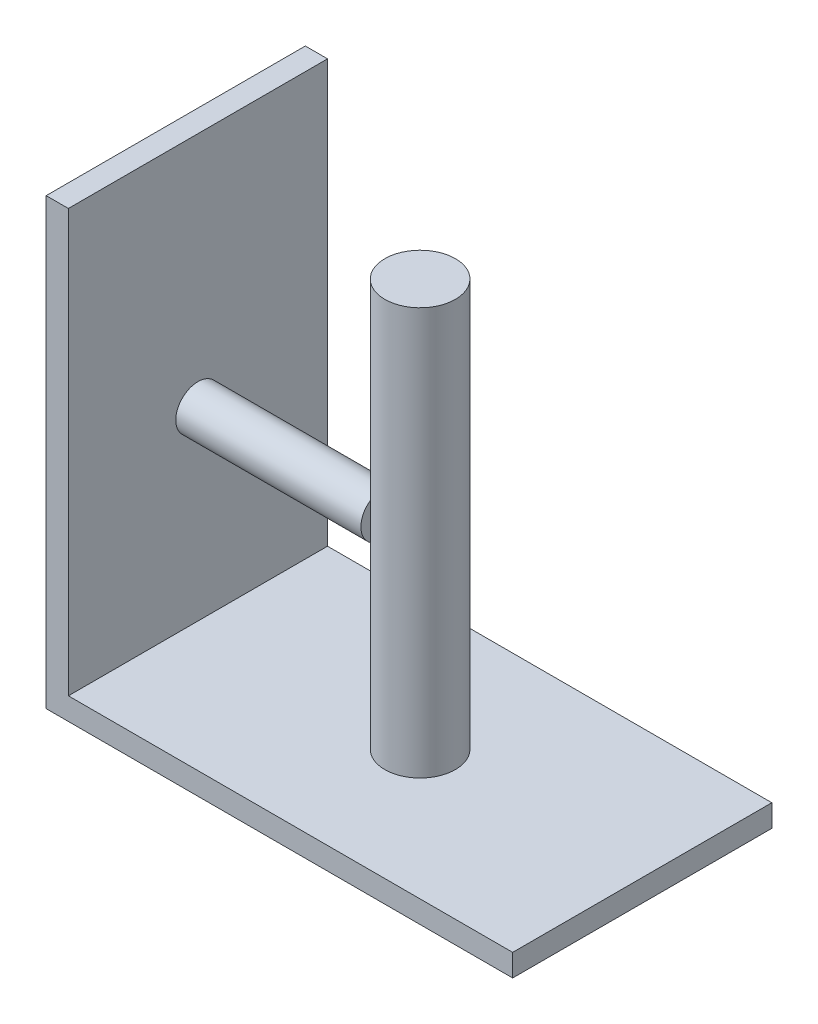
SolidWorks part; units mm, degrees
ref_plane "Alzado" through (0, 0, 0) normal (0, 0, 1) x (1, 0, 0)
ref_plane "Planta" through (0, 0, 0) normal (0, 1, 0) x (1, 0, 0)
ref_plane "Vista lateral" through (0, 0, 0) normal (1, 0, 0) x (0, 0, -1)
sketch "Croquis1" plane through (0, 0, 0) normal (0, 0, 1) x (1, 0, 0)
  line L1 (0, 0) -> (63, 0)
  line L2 (0, 0) -> (0, -3)
  line L3 (0, -3) -> (63, -3)
  line L4 (63, 0) -> (63, -3)
  line L5 (0, 0) -> (3, 0)
  line L6 (0, 0) -> (0, 57)
  line L7 (0, 57) -> (3, 57)
  line L8 (3, 0) -> (3, 57)
  dimension "D1" = 3
  dimension "D2" = 3
  dimension "D3" = 60
  dimension "D4" = 63
extrude "Saliente-Extruir1" add sketch "Croquis1" along normal mid plane 35 contours L5 L8 L7 L6 | L1 L4 L3 L2
sketch "Croquis2" plane through (3, 0, 0) normal (1, 0, 0) x (0, 0, -1)
  line L0 (-17.5, 0) -> (-17.5, 57) construction
  circle A0 centre (0, 25) radius 3
  dimension "D1" = 6
  dimension "D2" = 25
  dimension "D3" = 17.5
extrude "Saliente-Extruir2" add sketch "Croquis2" along normal blind 25
sketch "Croquis3" plane through (0, 0, 0) normal (0, 1, 0) x (1, 0, 0)
  line L0 (-4.1676, 0) -> (69.5182, 0) construction
  line L1 (33, 17.5) -> (33, -17.5) construction
  line L2 (3, 17.5) -> (63, 17.5) construction
  line L3 (3, -17.5) -> (63, -17.5) construction
  circle A0 centre (33, 0) radius 4.7625
  dimension "D1" = 9.525
extrude "Saliente-Extruir3" add sketch "Croquis3" along normal blind 55
